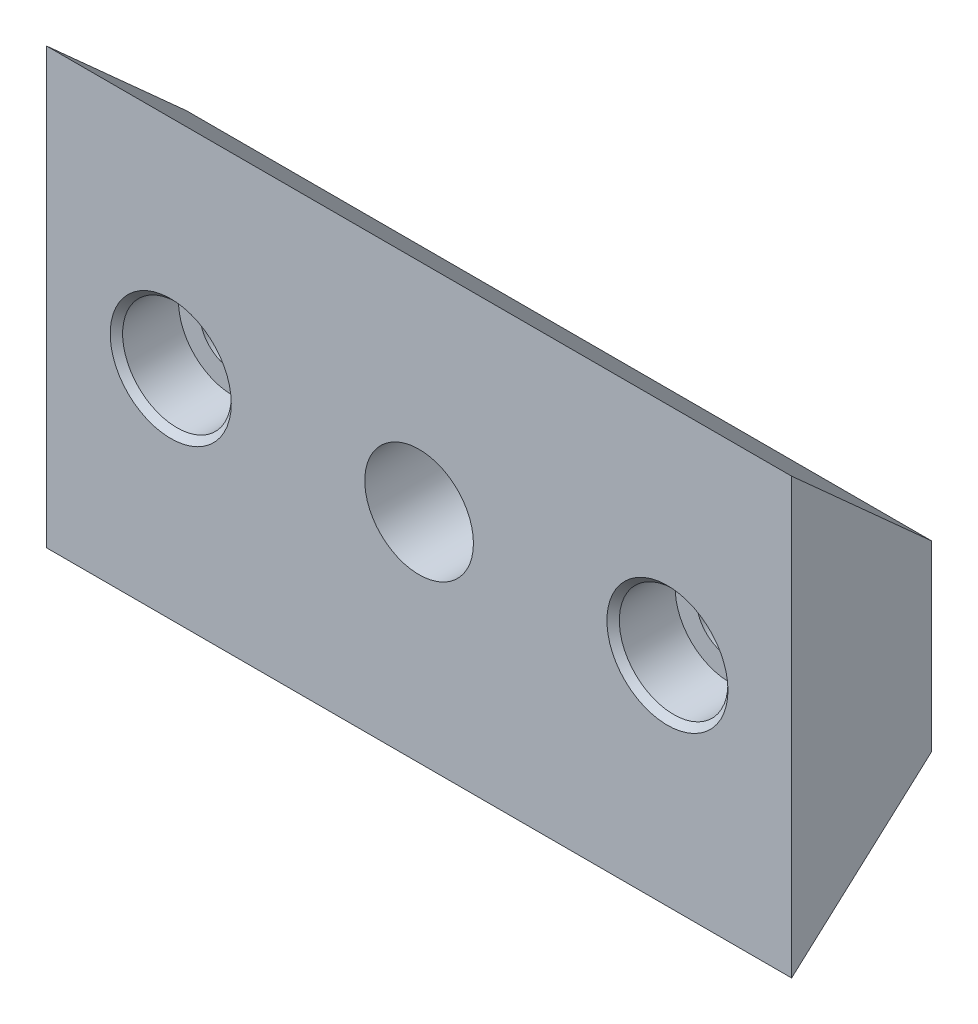
SolidWorks part; units mm, degrees
material "Gray Cast Iron"
ref_plane "Front" through (0, 0, 0) normal (0, 0, 1) x (1, 0, 0)
ref_plane "Top" through (0, 0, 0) normal (0, 1, 0) x (1, 0, 0)
ref_plane "Right" through (0, 0, 0) normal (1, 0, 0) x (0, 0, -1)
sketch "Sketch2" plane through (0, 0, 0) normal (1, 0, 0) x (0, 0, -1)
  line L0 (0, 0) -> (0, 44.45)
  line L1 (0, 44.45) -> (14.3002, 31.574)
  line L2 (14.3002, 31.574) -> (14.3002, 12.876)
  line L3 (14.3002, 12.876) -> (0, 0)
  dimension "D1" = 44.45
  dimension "D2" = 14.3002
  dimension "D3" = 48
  dimension "D4" = 48
extrude "Boss-Extrude1" add sketch "Sketch2" against normal blind 76.2
hole_wizard "CBORE for 1/4 Socket Head Cap Screw1" positions "Sketch4" profile "Sketch3" counterbore size "1/4" standard "ANSI Inch" end condition through all
sketch "Sketch4" plane through (0, 0, 0) normal (0, 0, 1) x (1, 0, 0)
  line L0 (-76.2, 44.45) -> (-76.2, 0) construction
  line L1 (-76.2, 44.45) -> (0, 44.45) construction
  point P0 (-63.5, 22.225)
  point P2 (-12.7, 22.225)
  dimension "D1" = 12.7
  dimension "D2" = 50.8
  dimension "D3" = 22.225
sketch "Sketch3" plane through (-63.5, 22.225, 0) normal (1, 0, 0) x (0, -1, 0)
  line L0 (0, 0) -> (0, 14.3002)
  line L1 (0, 14.3002) -> (3.3782, 14.3002)
  line L3 (3.3782, 14.3002) -> (3.3782, 6.35)
  line L4 (5.5562, 6.35) -> (3.3782, 6.35)
  line L5 (5.5562, 6.35) -> (5.5562, 0.635)
  line L6 (5.5562, 0.635) -> (6.1912, 0)
  line L7 (6.1912, 0) -> (0, 0)
  line L8 (-5.5562, 0.635) -> (-6.1912, 0) construction
  line L11 (0, -6.35) -> (0, 107.95) construction
  dimension "Thru Hole Dia." = 6.7564
  dimension "Thru Hole Depth" = 14.3002
  dimension "C'Bore Dia." = 11.1125
  dimension "C'Bore Depth" = 6.35
  dimension "Near C'Sink Dia." = 12.3825
  dimension "Near C'Sink Angle" = 90
hole_wizard "7/16 (0.4375) Diameter Hole1" positions "Sketch6" profile "Sketch5" hole size "7/16" standard "ANSI Inch" end condition through all
sketch "Sketch6" plane through (0, 0, 0) normal (0, 0, 1) x (1, 0, 0)
  line L0 (-76.2, 44.45) -> (-76.2, 0) construction
  circle A0 centre (-63.5, 22.225) radius 3.3782 construction
  point P0 (-38.1, 22.225)
  point P14 (-76.2, 22.225)
  dimension "D1" = 25.4
sketch "Sketch5" plane through (-38.1, 22.225, 0) normal (1, 0, 0) x (0, -1, 0)
  line L0 (0, 0) -> (0, 14.3002)
  line L1 (0, 14.3002) -> (5.5562, 14.3002)
  line L2 (5.5562, 14.3002) -> (5.5562, 0)
  line L5 (5.5562, 0) -> (0, 0)
  line L11 (0, -6.35) -> (0, 107.95) construction
  dimension "Thru Hole Dia." = 11.1125
  dimension "Thru Hole Depth" = 14.3002
sketch "Sketch8" plane through (0, 0, 0) normal (0, 0, 1) x (1, 0, 0)
  line L0 (-76.2, 22.225) -> (0, 22.225) construction
  line L1 (-76.2, 44.45) -> (-76.2, 0) construction
  line L2 (0, 44.45) -> (0, 0) construction
